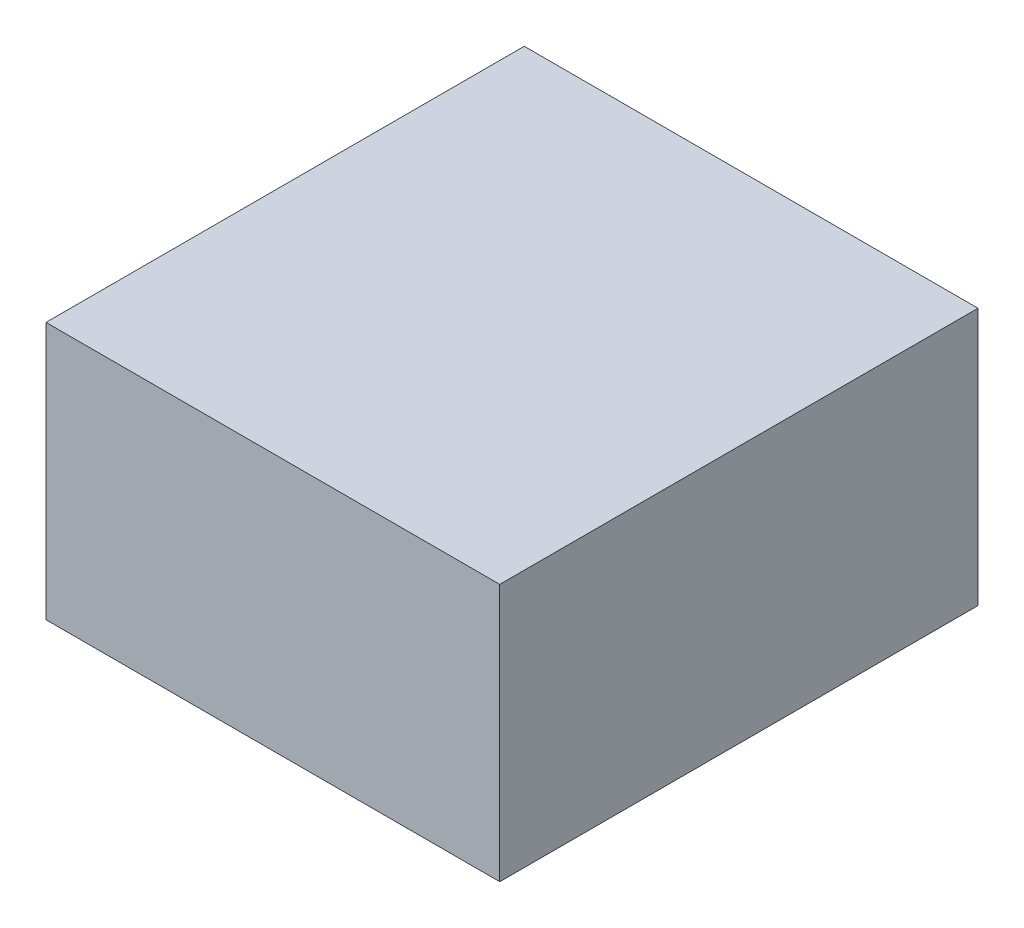
SolidWorks part; units mm, degrees
ref_plane "Front Plane" through (0, 0, 0) normal (0, 0, 1) x (1, 0, 0)
ref_plane "Top Plane" through (0, 0, 0) normal (0, 1, 0) x (1, 0, 0)
ref_plane "Right Plane" through (0, 0, 0) normal (1, 0, 0) x (0, 0, -1)
sketch "Sketch1" plane through (0, 0, 0) normal (0, 1, 0) x (1, 0, 0)
  line L1 (-185, -195) -> (185, -195)
  line L2 (-185, -195) -> (-185, 195)
  line L3 (-185, 195) -> (185, 195)
  line L4 (185, -195) -> (185, 195)
  line L5 (-185, -195) -> (185, 195) construction
  line L6 (-185, 195) -> (185, -195) construction
  point P0 (0, 0)
  dimension "D1" = 390
  dimension "D2" = 370
extrude "Boss-Extrude1" add sketch "Sketch1" along normal blind 210
